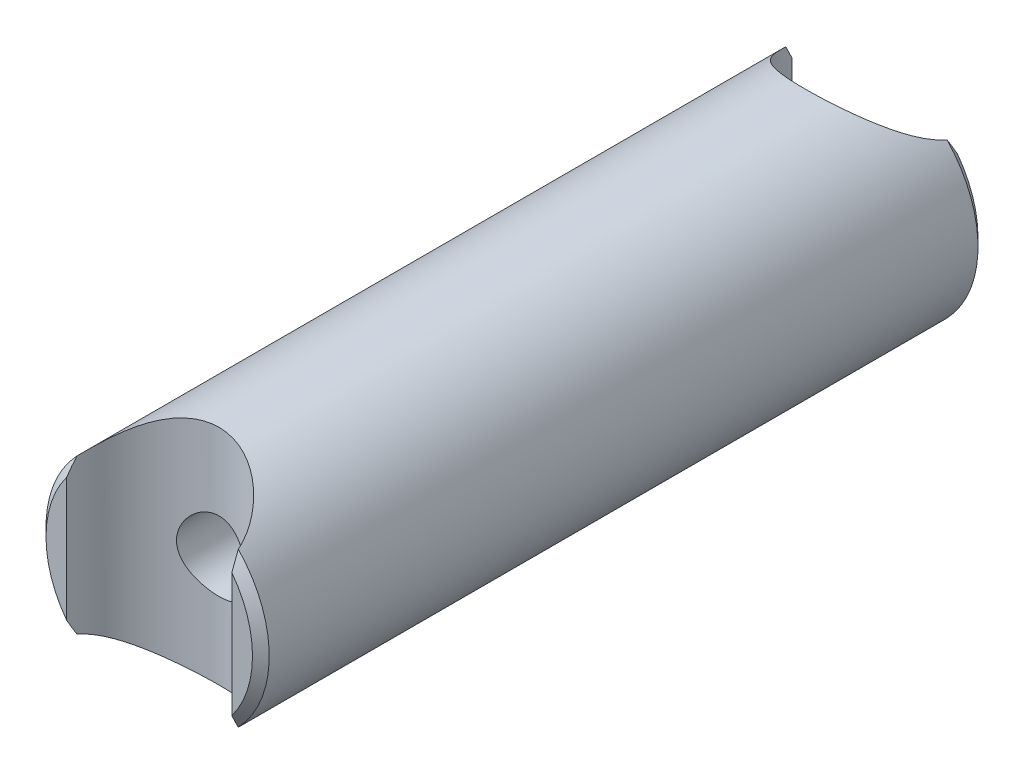
SolidWorks part; units mm, degrees
material "3.3535 (EN-AW 5754)"
ref_plane "Front" through (0, 0, 0) normal (0, 0, 1) x (1, 0, 0)
ref_plane "Top" through (0, 0, 0) normal (0, 1, 0) x (1, 0, 0)
ref_plane "Right" through (0, 0, 0) normal (1, 0, 0) x (0, 0, -1)
sketch "Esquisse1" plane through (0, 0, 0) normal (0, 0, 1) x (1, 0, 0)
  circle A0 centre (0, 0) radius 4
  circle A1 centre (0, 0) radius 1.25
  dimension "D1" = 8
  dimension "D2" = 2.5
extrude "Boss.-Extru.1" add sketch "Esquisse1" along normal mid plane 26
chamfer "Chanfrein1" distance 0.3 angle 45 2 edges at (4, 0, -13) (4, 0, 13)
sketch "Esquisse2" plane through (0, 0, 0) normal (0, 1, 0) x (1, 0, 0)
  line L0 (-50, 0) -> (50, 0) construction
  circle A0 centre (0, 13.5) radius 3
  circle A4 centre (0, -13.5) radius 3
  dimension "D2" = 27
  dimension "D3" = 6
extrude "Enlèv. mat.-Extru.1" cut sketch "Esquisse2" against normal through all both and the other way through all
